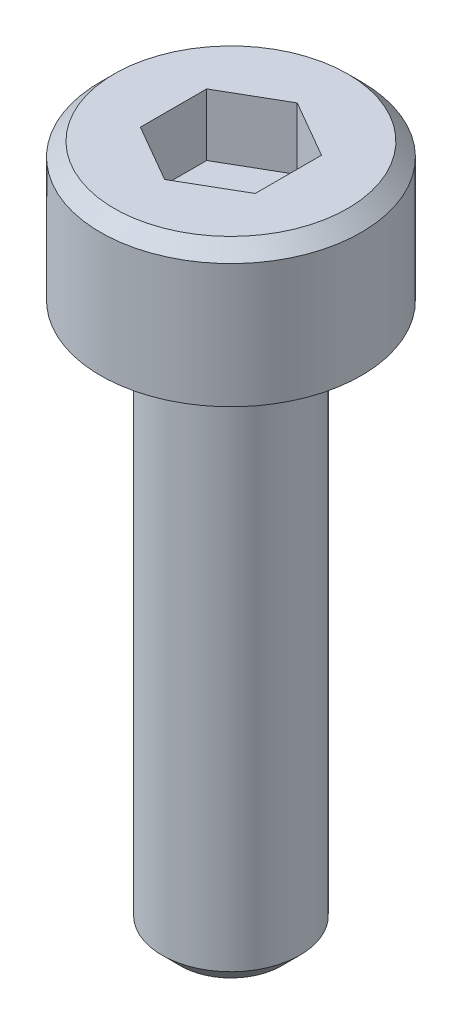
SolidWorks part; units mm, degrees
ref_plane "Front Plane" through (0, 0, 0) normal (0, 0, 1) x (1, 0, 0)
ref_plane "Top Plane" through (0, 0, 0) normal (0, 1, 0) x (1, 0, 0)
ref_plane "Right Plane" through (0, 0, 0) normal (1, 0, 0) x (0, 0, -1)
sketch "Sketch1" plane through (0, 0, 0) normal (0, 0, 1) x (1, 0, 0)
  line L0 (0, -12) -> (1.1, -12)
  line L1 (1.1, -12) -> (1.5, -11.6)
  line L2 (1.5, -11.6) -> (1.5, 0)
  line L3 (1.5, 0) -> (2.84, 0)
  line L4 (2.84, 0) -> (2.84, 2.7)
  line L5 (2.84, 2.7) -> (2.54, 3)
  line L6 (2.54, 3) -> (0, 3)
  line L7 (0, 3) -> (0, -12)
  line L8 (0, -10) -> (0, 1000) construction
revolve "Revolve1" add sketch "Sketch1" angle 360 about L8
cosmetic thread "Cosmetic Thread1" parameters "D1"=11.6, "D2"=2.4588
ref_plane "Plane1" through (0, 3, 0) normal (0, 1, 0) x (1, 0, 0)
sketch "Sketch2" plane through (0, 3, 0) normal (0, 1, 0) x (1, 0, 0)
  line L0 (1.25, -0.7217) -> (0, -1.4434)
  line L1 (0, -1.4434) -> (-1.25, -0.7217)
  line L2 (-1.25, -0.7217) -> (-1.25, 0.7217)
  line L3 (-1.25, 0.7217) -> (0, 1.4434)
  line L4 (0, 1.4434) -> (1.25, 0.7217)
  line L5 (1.25, 0.7217) -> (1.25, -0.7217)
extrude "Cut-Extrude1" cut sketch "Sketch2" against normal blind 1.35
